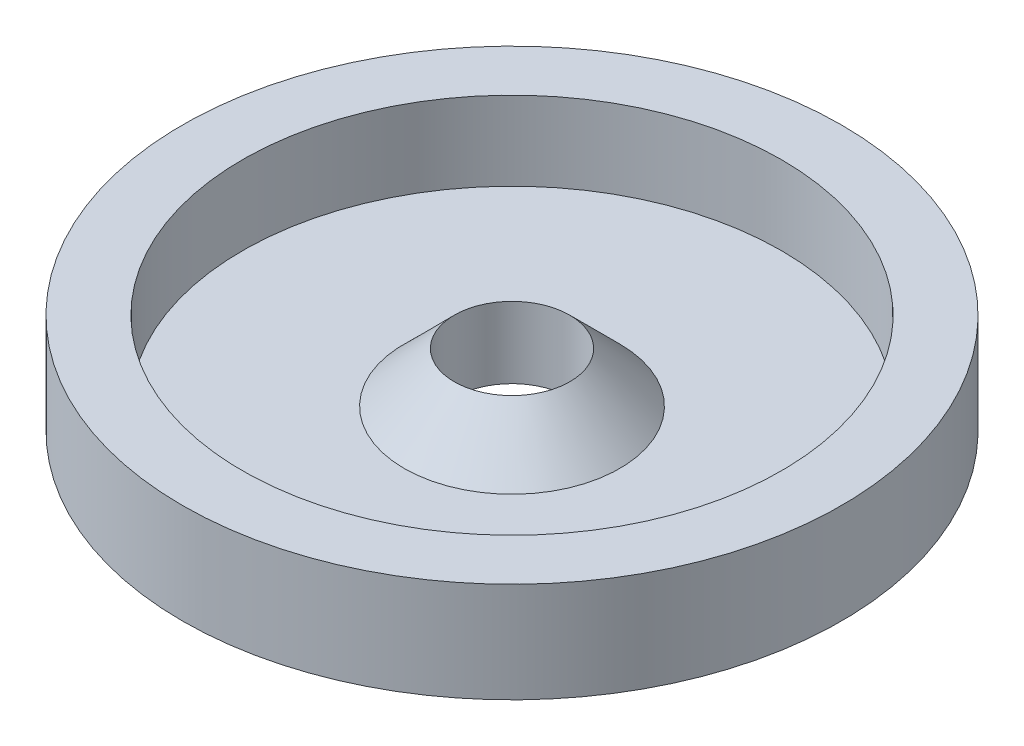
SolidWorks part; units mm, degrees
ref_plane "Front" through (0, 0, 0) normal (0, 0, 1) x (1, 0, 0)
ref_plane "Top" through (0, 0, 0) normal (0, 1, 0) x (1, 0, 0)
ref_plane "Right" through (0, 0, 0) normal (1, 0, 0) x (0, 0, -1)
sketch "Sketch1" plane through (0, 0, 0) normal (0, 0, 1) x (1, 0, 0)
  line L0 (0, -10.8626) -> (0, 14.7653) construction
  line L1 (3.75, 0) -> (21.4, 0)
  line L2 (21.4, 0) -> (21.4, 6.5)
  line L3 (21.4, 6.5) -> (17.5, 6.5)
  line L4 (17.5, 6.5) -> (17.5, 1.38)
  line L5 (17.5, 1.38) -> (7, 1.38)
  line L6 (7, 1.38) -> (3.75, 4.63)
  line L7 (3.75, 4.63) -> (3.75, 0)
  dimension "D1" = 21.4
  dimension "D2" = 3.75
  dimension "D3" = 7
  dimension "D4" = 45
  dimension "D5" = 1.38
  dimension "D6" = 6.5
  dimension "D7" = 17.5
revolve "Revolve1" add sketch "Sketch1" angle 360 about L0
